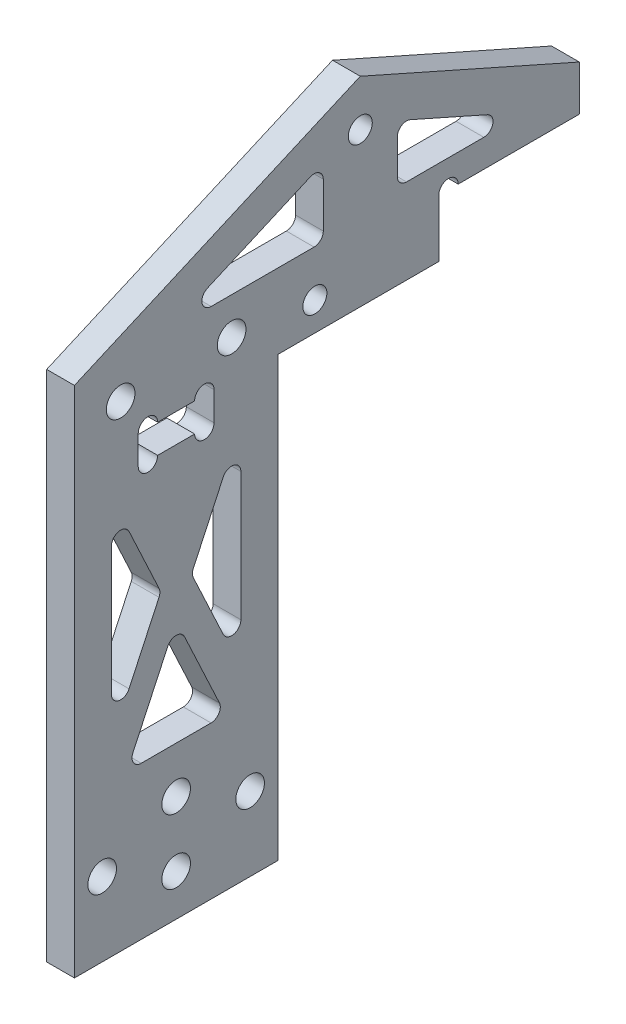
SolidWorks part; units mm, degrees
material "Thornel Mat VMA"
ref_plane "前视基准面" through (0, 0, 0) normal (0, 0, 1) x (1, 0, 0)
ref_plane "上视基准面" through (0, 0, 0) normal (0, 1, 0) x (1, 0, 0)
ref_plane "右视基准面" through (0, 0, 0) normal (1, 0, 0) x (0, 0, -1)
sketch "草图1" plane through (0, 0, 0) normal (1, 0, 0) x (0, 0, -1)
  line L0 (0, 0) -> (0, 14.8872) construction
  line L1 (11, -27.75) -> (-11, -27.75)
  line L2 (11, -27.75) -> (11, 19.65)
  line L3 (11, 27.75) -> (-11, 27.75) construction
  line L4 (-11, -27.75) -> (-11, 27.75)
  line L5 (11, -27.75) -> (-11, 27.75) construction
  line L6 (11, 27.75) -> (-11, -27.75) construction
  line L7 (-8, -19.75) -> (3.7687, -19.75) construction
  line L8 (5.3447, 18.75) -> (0, 7.2971) construction
  line L9 (7, -11.25) -> (-7, -11.25) construction
  line L10 (7, -11.25) -> (7, 18.75) construction
  line L11 (7, 18.75) -> (-7, 18.75) construction
  line L12 (-7, -11.25) -> (-7, 18.75) construction
  line L13 (7, -11.25) -> (-7, 18.75) construction
  line L14 (7, 18.75) -> (-7, -11.25) construction
  line L15 (-5.3447, -11.25) -> (0, 0.2029)
  line L16 (-5.3447, 18.75) -> (0, 7.2971) construction
  line L17 (-7, 15.2029) -> (-1.6553, 3.75)
  line L18 (-7, 15.2029) -> (-7, -7.7029)
  line L19 (-5.3447, -11.25) -> (5.3447, -11.25)
  line L20 (7, -7.7029) -> (7, 15.2029)
  line L21 (-5.3447, 18.75) -> (5.3447, 18.75) construction
  line L22 (-1.6553, 3.75) -> (-7, -7.7029)
  line L23 (1.6553, 3.75) -> (7, -7.7029)
  line L24 (1.6553, 3.75) -> (7, 15.2029)
  line L25 (0, 0.2029) -> (5.3447, -11.25)
  line L26 (19.9131, 36.2485) -> (36, 22.75) construction
  line L27 (4.1, 16.7) -> (-4.1, 16.7)
  line L28 (4.1, 16.7) -> (4.1, 19.8)
  line L29 (4.1, 19.8) -> (-4.1, 19.8)
  line L30 (-4.1, 16.7) -> (-4.1, 19.8)
  line L31 (4.1, 16.7) -> (-4.1, 19.8) construction
  line L32 (4.1, 19.8) -> (-4.1, 16.7) construction
  line L33 (43.6, 19.65) -> (28.4, 19.65) construction
  line L34 (43.6, 19.65) -> (43.6, 25.85)
  line L35 (43.6, 25.85) -> (28.4, 25.85)
  line L36 (28.4, 19.65) -> (28.4, 25.85)
  line L37 (43.6, 19.65) -> (28.4, 25.85) construction
  line L38 (43.6, 25.85) -> (28.4, 19.65) construction
  line L39 (36, 22.75) -> (27.6241, 22.75) construction
  line L40 (28.4, 19.65) -> (11, 19.65)
  line L41 (-11, 27.75) -> (19.9131, 41.2485)
  line L42 (19.9131, 41.2485) -> (45.6, 29.85)
  line L43 (45.6, 29.85) -> (45.6, 19.65)
  line L44 (45.6, 19.65) -> (43.6, 19.65)
  line L45 (15.9131, 35.1372) -> (-1.0043, 27.75)
  line L46 (-1.0043, 27.75) -> (15.9131, 27.75)
  line L47 (15.9131, 27.75) -> (15.9131, 35.1372)
  line L48 (23.9131, 35.0974) -> (23.9131, 28.85)
  line L49 (23.9131, 28.85) -> (37.9918, 28.85)
  line L50 (37.9918, 28.85) -> (23.9131, 35.0974)
  circle A0 centre (-6, 23.75) radius 1.55
  circle A1 centre (6, 23.75) radius 1.55
  circle A2 centre (0, -16.25) radius 1.55
  circle A3 centre (0, -23.25) radius 1.55
  circle A4 centre (8, -19.75) radius 1.55
  circle A5 centre (-8, -19.75) radius 1.55
  circle A6 centre (-3.05, 16.7) radius 1.05
  circle A7 centre (3.05, 16.7) radius 1.05
  circle A8 centre (3.05, 19.8) radius 1.05
  circle A9 centre (-3.05, 19.8) radius 1.05
  circle A10 centre (15, 22.75) radius 1.3
  circle A11 centre (19.9131, 36.2485) radius 1.3
  circle A12 centre (36, 22.75) radius 21 construction
  circle A13 centre (42.55, 25.85) radius 1.05 construction
  circle A14 centre (29.45, 25.85) radius 1.05
  point P0 (0, 0)
  point P20 (0, 3.75)
  point P34 (0, 18.25)
  point P55 (36, 22.75)
  dimension "D2" = 3.1
  dimension "D16" = 2.1
  dimension "D20" = 2.6
  dimension "D21" = 42
  dimension "D1" = 12
  dimension "D3" = 51.5
  dimension "D4" = 4
  dimension "D5" = 5
  dimension "D6" = 8
  dimension "D7" = 7
  dimension "D8" = 8
  dimension "D9" = 5
  dimension "D10" = 5
  dimension "D11" = 4
  dimension "D12" = 8.2
  dimension "D13" = 3
  dimension "D14" = 3.1
  dimension "D15" = 5.5
  dimension "D17" = 4.5
  dimension "D18" = 6.2
  dimension "D19" = 15.2
  dimension "D22" = 40
  dimension "D23" = 36
  dimension "D24" = 2
  dimension "D25" = 4
  dimension "D26" = 5
  dimension "D27" = 4
  dimension "D28" = 4
  dimension "D29" = 3
  dimension "D30" = 4
  dimension "D31" = 4
extrude "凸台-拉伸1" add sketch "草图1" along normal blind 3 contours L4 L1 L2 L3 A9 L29 A8 L28 A7 L27 A6 L30 A5 A4 A3 A2 L15 L25 L19 L23 L24 L20 L17 L22 L18 A0 A1
fillet "圆角1" radius 1 15 edges at (1.5, -11.25, 5.3447) (1.5, -11.25, -5.3447) (1.5, 0.2029, 0) (1.5, -7.7029, -7) (1.5, 15.2029, -7) (1.5, 3.75, -1.6553) (1.5, -7.7029, 7) (1.5, 3.75, 1.6553) (1.5, 15.2029, 7) (1.5, 28.85, -23.9131) (1.5, 28.85, -37.9918) (1.5, 35.0974, -23.9131) (1.5, 27.75, -15.9131) (1.5, 35.1372, -15.9131) (1.5, 27.75, 1.0043)
sketch "草图2" plane through (3, 0, 0) normal (1, 0, 0) x (0, 0, -1)
  line L1 (51.1689, 44.5783) -> (43.6, 44.5783)
  line L2 (51.1689, 44.5783) -> (51.1689, 19.65)
  line L3 (51.1689, 19.65) -> (43.6, 19.65)
  line L4 (43.6, 44.5783) -> (43.6, 19.65)
  line L5 (51.1689, 44.5783) -> (43.6, 19.65) construction
  line L6 (51.1689, 19.65) -> (43.6, 44.5783) construction
  point P0 (47.3845, 32.1142)
extrude "切除-拉伸1" cut sketch "草图2" against normal blind 10
